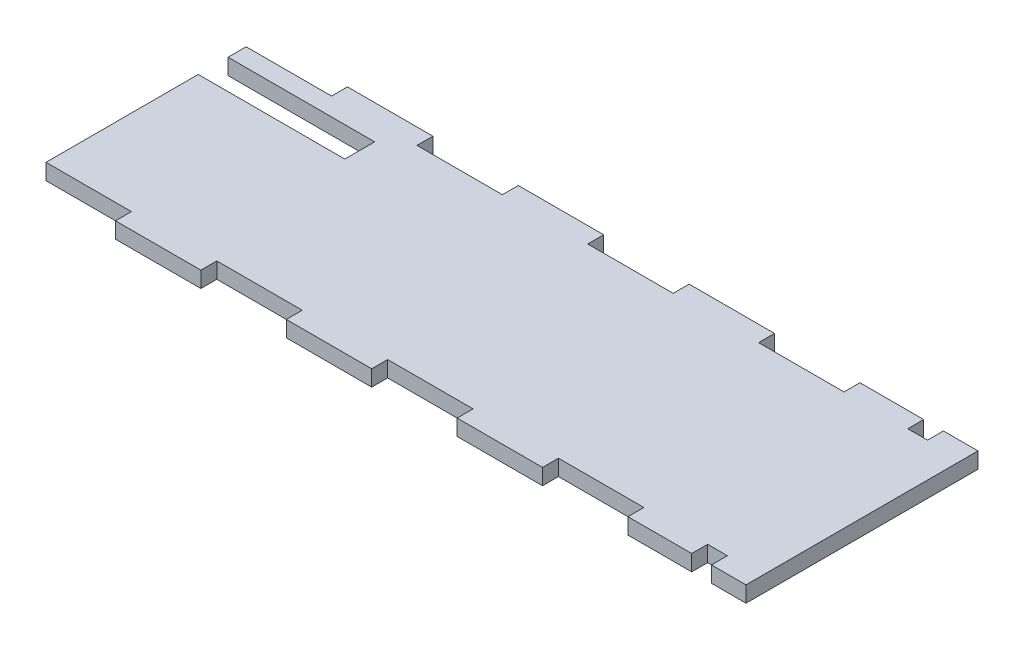
SolidWorks part; units mm, degrees
material "Maple"
ref_plane "Front Plane" through (0, 0, 0) normal (0, 0, 1) x (1, 0, 0)
ref_plane "Top Plane" through (0, 0, 0) normal (0, 1, 0) x (1, 0, 0)
ref_plane "Right Plane" through (0, 0, 0) normal (1, 0, 0) x (0, 0, -1)
sketch "Sketch1" plane through (0, 0, 0) normal (0, 1, 0) x (1, 0, 0)
  line L0 (-55, 0) -> (55, 0) construction
  line L1 (-54.3052, -23.114) -> (-37.2872, -23.114)
  line L2 (-71.3232, -19.939) -> (-71.3232, 19.939)
  line L3 (-54.3052, 23.114) -> (-37.2872, 23.114)
  line L4 (71.3232, -23.114) -> (71.3232, 23.114)
  line L5 (-61.5261, -19.939) -> (71.3232, 23.114) construction
  line L6 (-61.5261, 19.939) -> (71.3232, -23.114) construction
  line L9 (-71.3232, -19.939) -> (-54.3052, -19.939)
  line L10 (-54.3052, -23.114) -> (-54.3052, -19.939)
  line L12 (-37.2872, -23.114) -> (-37.2872, -19.939)
  line L13 (-37.2872, -19.939) -> (-20.2692, -19.939)
  line L14 (-20.2692, -23.114) -> (-20.2692, -19.939)
  line L16 (-3.2512, -23.114) -> (-3.2512, -19.939)
  line L17 (-3.2512, -19.939) -> (13.7668, -19.939)
  line L18 (13.7668, -23.114) -> (13.7668, -19.939)
  line L20 (30.7848, -23.114) -> (30.7848, -19.939)
  line L21 (30.7848, -19.939) -> (47.8028, -19.939)
  line L22 (47.8028, -23.114) -> (47.8028, -19.939)
  line L24 (60.5028, -23.114) -> (60.5028, -19.939)
  line L25 (60.5028, -19.939) -> (64.4398, -19.939)
  line L26 (64.4398, -23.114) -> (64.4398, -19.939)
  line L27 (64.4398, 23.114) -> (64.4398, 19.939)
  line L28 (60.5028, 19.939) -> (64.4398, 19.939)
  line L29 (60.5028, 23.114) -> (60.5028, 19.939)
  line L30 (47.8028, 23.114) -> (47.8028, 19.939)
  line L31 (30.7848, 19.939) -> (47.8028, 19.939)
  line L32 (30.7848, 23.114) -> (30.7848, 19.939)
  line L33 (13.7668, 23.114) -> (13.7668, 19.939)
  line L34 (-3.2512, 19.939) -> (13.7668, 19.939)
  line L35 (-3.2512, 23.114) -> (-3.2512, 19.939)
  line L36 (-20.2692, 23.114) -> (-20.2692, 19.939)
  line L37 (-37.2872, 23.114) -> (-37.2872, 19.939)
  line L38 (-37.2872, 19.939) -> (-20.2692, 19.939)
  line L39 (-54.3052, 23.114) -> (-54.3052, 19.939)
  line L40 (-71.3232, 19.939) -> (-54.3052, 19.939)
  line L41 (-20.2692, 23.114) -> (-3.2512, 23.114)
  line L42 (13.7668, 23.114) -> (30.7848, 23.114)
  line L43 (47.8028, 23.114) -> (60.5028, 23.114)
  line L44 (64.4398, 23.114) -> (71.3232, 23.114)
  line L45 (64.4398, -23.114) -> (71.3232, -23.114)
  line L46 (47.8028, -23.114) -> (60.5028, -23.114)
  line L47 (13.7668, -23.114) -> (30.7848, -23.114)
  line L48 (-20.2692, -23.114) -> (-3.2512, -23.114)
  point P0 (0, 0)
  dimension "D2" = 142.6464
  dimension "D3" = 17.018
  dimension "D4" = 3.175
  dimension "D5" = 17.018
  dimension "D6" = 3.175
  dimension "D7" = 17.018
  dimension "D8" = 17.018
  dimension "D9" = 3.175
  dimension "D10" = 17.018
  dimension "D11" = 17.018
  dimension "D12" = 17.018
  dimension "D13" = 12.7
  dimension "D14" = 3.937
  dimension "D15" = 3.175
  dimension "D16" = 46.228
  dimension "D17" = 3.175
extrude "Boss-Extrude1" add sketch "Sketch1" along normal blind 3.175
sketch "Sketch2" plane through (0, 3.175, 0) normal (0, 1, 0) x (1, 0, 0)
  line L6 (-71.3232, 19.939) -> (-71.3232, -19.939) construction
  line L7 (-71.3232, 16.3322) -> (-42.1132, 16.3322)
  line L8 (-71.3232, 16.3322) -> (-71.3232, 10.3886)
  line L9 (-71.3232, 10.3886) -> (-42.1132, 10.3886)
  line L10 (-42.1132, 16.3322) -> (-42.1132, 10.3886)
  line L11 (-37.2872, 23.114) -> (-54.3052, 23.114) construction
  dimension "D4" = 29.21
  dimension "D5" = 5.9436
  dimension "D6" = 6.7818
extrude "Cut-Extrude2" cut sketch "Sketch2" against normal blind 4.064
